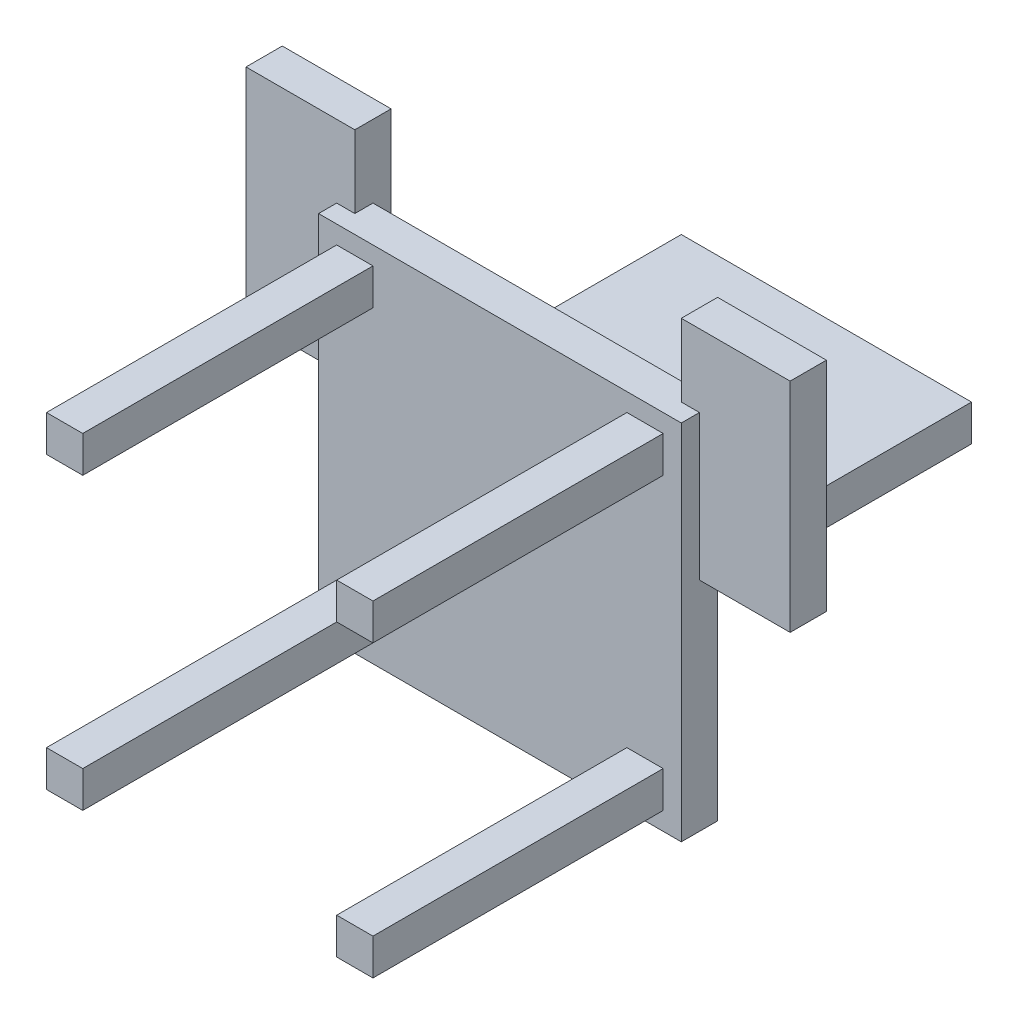
SolidWorks part; units mm, degrees
ref_plane "前视基准面" through (0, 0, 0) normal (0, 0, 1) x (1, 0, 0)
ref_plane "上视基准面" through (0, 0, 0) normal (0, 1, 0) x (1, 0, 0)
ref_plane "右视基准面" through (0, 0, 0) normal (1, 0, 0) x (0, 0, -1)
other "Configuration Table"
sketch "草图1" plane through (0, 0, 0) normal (0, 0, 1) x (1, 0, 0)
  line L1 (-250, -250) -> (250, -250)
  line L2 (-250, -250) -> (-250, 250)
  line L3 (-250, 250) -> (250, 250)
  line L4 (250, -250) -> (250, 250)
  line L5 (-250, -250) -> (250, 250) construction
  line L6 (-250, 250) -> (250, -250) construction
  point P0 (0, 0)
extrude "凸台-拉伸1" add sketch "草图1" along normal blind 50
sketch "草图2" plane through (0, 0, 0) normal (0, 0, 1) x (1, 0, 0)
  line L1 (-225, -225) -> (-175, -225)
  line L2 (-225, -225) -> (-225, -175)
  line L3 (-225, -175) -> (-175, -175)
  line L4 (-175, -225) -> (-175, -175)
  line L5 (-225, -225) -> (-175, -175) construction
  line L6 (-225, -175) -> (-175, -225) construction
  point P0 (-200, -200)
extrude "凸台-拉伸2" add sketch "草图2" along normal blind 450
sketch "草图3" plane through (0, 0, 0) normal (0, 0, 1) x (1, 0, 0)
  line L1 (175, -225) -> (225, -225)
  line L2 (175, -225) -> (175, -175)
  line L3 (175, -175) -> (225, -175)
  line L4 (225, -225) -> (225, -175)
  line L5 (175, -225) -> (225, -175) construction
  line L6 (175, -175) -> (225, -225) construction
  point P0 (200, -200)
extrude "凸台-拉伸3" add sketch "草图3" along normal blind 450
sketch "草图4" plane through (0, 0, 0) normal (0, 0, 1) x (1, 0, 0)
  line L1 (-225, 175) -> (-175, 175)
  line L2 (-225, 175) -> (-225, 225)
  line L3 (-225, 225) -> (-175, 225)
  line L4 (-175, 175) -> (-175, 225)
  line L5 (-225, 175) -> (-175, 225) construction
  line L6 (-225, 225) -> (-175, 175) construction
  point P0 (-200, 200)
extrude "凸台-拉伸4" add sketch "草图4" along normal blind 450
sketch "草图5" plane through (0, 0, 0) normal (0, 0, 1) x (1, 0, 0)
  line L1 (175, 175) -> (225, 175)
  line L2 (175, 175) -> (175, 225)
  line L3 (175, 225) -> (225, 225)
  line L4 (225, 175) -> (225, 225)
  line L5 (175, 175) -> (225, 225) construction
  line L6 (175, 225) -> (225, 175) construction
  point P0 (200, 200)
extrude "凸台-拉伸5" add sketch "草图5" along normal blind 450
sketch "草图6" plane through (0, 0, 0) normal (0, 0, -1) x (-1, 0, 0)
  line L1 (-200, -25) -> (200, -25)
  line L2 (-200, -25) -> (-200, 25)
  line L3 (-200, 25) -> (200, 25)
  line L4 (200, -25) -> (200, 25)
  line L5 (-200, -25) -> (200, 25) construction
  line L6 (-200, 25) -> (200, -25) construction
  point P0 (0, 0)
extrude "凸台-拉伸6" add sketch "草图6" along normal blind 400
sketch "草图7" plane through (225, 0, 0) normal (1, 0, 0) x (0, 0, -1)
  line L0 (0, -250) -> (0, 250) construction
  line L1 (-25, 50) -> (25, 50)
  line L2 (-25, 50) -> (-25, 350)
  line L3 (-25, 350) -> (25, 350)
  line L4 (25, 50) -> (25, 350)
  line L5 (-25, 50) -> (25, 350) construction
  line L6 (-25, 350) -> (25, 50) construction
  point P0 (0, 200)
extrude "凸台-拉伸7" add sketch "草图7" along normal blind 150
sketch "草图8" plane through (-225, 0, 0) normal (-1, 0, 0) x (0, 0, 1)
  line L0 (0, 50) -> (0, 250) construction
  line L1 (-25, 50) -> (25, 50)
  line L2 (-25, 50) -> (-25, 350)
  line L3 (-25, 350) -> (25, 350)
  line L4 (25, 50) -> (25, 350)
  line L5 (-25, 50) -> (25, 350) construction
  line L6 (-25, 350) -> (25, 50) construction
  point P0 (0, 200)
extrude "凸台-拉伸8" add sketch "草图8" along normal blind 150
